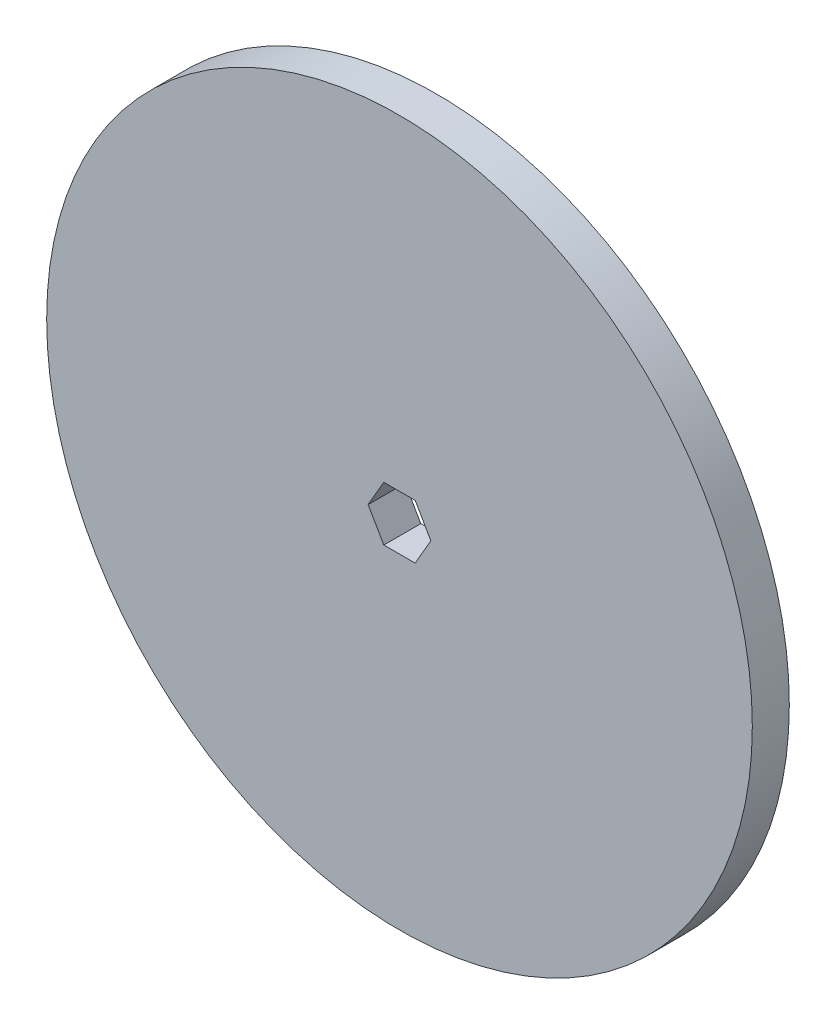
SolidWorks part; units mm, degrees
ref_plane "Front Plane" through (0, 0, 0) normal (0, 0, 1) x (1, 0, 0)
ref_plane "Top Plane" through (0, 0, 0) normal (0, 1, 0) x (1, 0, 0)
ref_plane "Right Plane" through (0, 0, 0) normal (1, 0, 0) x (0, 0, -1)
sketch "Sketch1" plane through (0, 0, 0) normal (0, 0, 1) x (1, 0, 0)
  circle A0 centre (0, 0) radius 57.15
  dimension "D1" = 114.3
extrude "Boss-Extrude1" add sketch "Sketch1" along normal blind 5.9944
sketch "Sketch2" plane through (0, 0, 5.9944) normal (0, 0, 1) x (1, 0, 0)
  line L1 (5.08, 0) -> (2.54, 4.3994)
  line L2 (2.54, 4.3994) -> (-2.54, 4.3994)
  line L3 (-2.54, 4.3994) -> (-5.08, 0)
  line L4 (-5.08, 0) -> (-2.54, -4.3994)
  line L5 (-2.54, -4.3994) -> (2.54, -4.3994)
  line L6 (2.54, -4.3994) -> (5.08, 0)
  circle A0 centre (0, 0) radius 4.3994 construction
  dimension "D1" = 5.08
extrude "Cut-Extrude1" cut sketch "Sketch2" against normal through all
